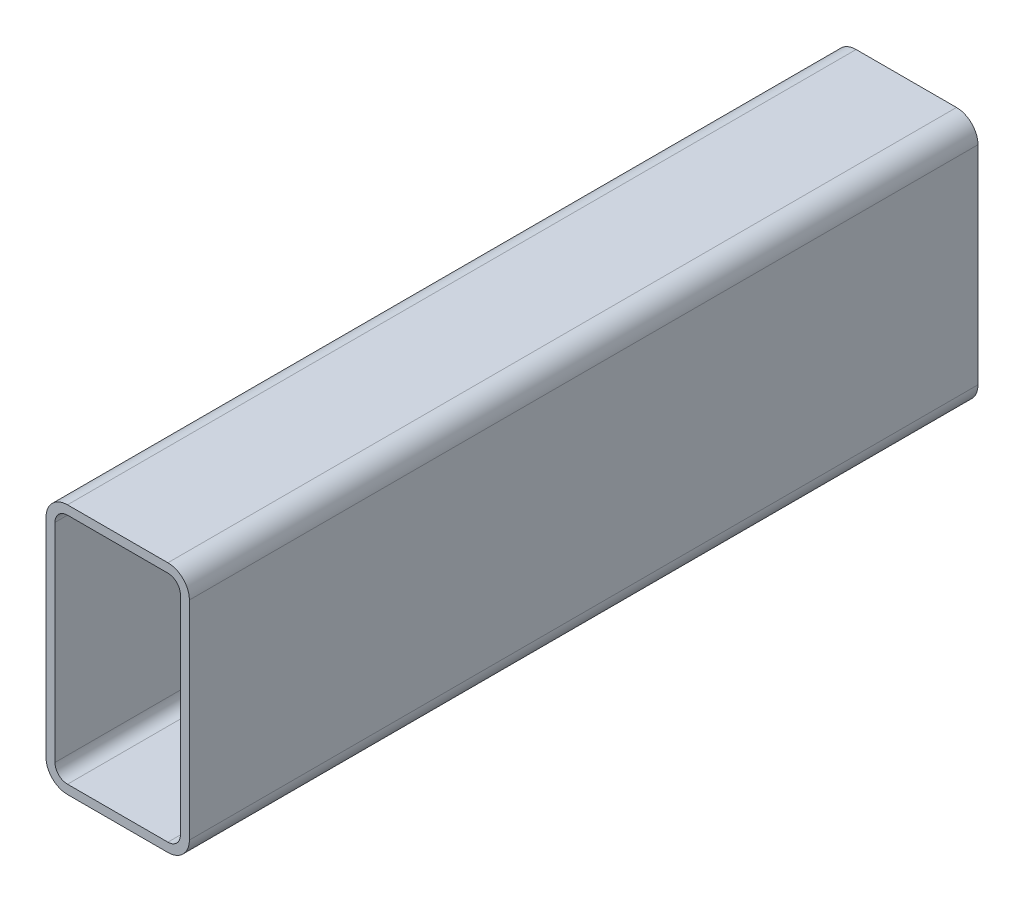
SolidWorks part; units mm, degrees
material "1.0037 (S235JR)"
ref_plane "Płaszczyzna przednia" through (0, 0, 0) normal (0, 0, 1) x (1, 0, 0)
ref_plane "Płaszczyzna górna" through (0, 0, 0) normal (0, 1, 0) x (1, 0, 0)
ref_plane "Płaszczyzna prawa" through (0, 0, 0) normal (1, 0, 0) x (0, 0, -1)
sketch "Szkic2" plane through (0, 0, 0) normal (0, 0, 1) x (1, 0, 0)
  line L0 (10, 450) -> (70, 450) construction
  line L1 (12, 450) -> (68, 450)
  line L2 (0, 438) -> (0, 322)
  line L3 (12, 310) -> (68, 310)
  line L4 (80, 438) -> (80, 322)
  line L5 (0, 450) -> (0, 0) construction
  line L6 (80, 450) -> (80, 0) construction
  line L7 (12, 445) -> (68, 445)
  line L8 (75, 438) -> (75, 322)
  line L9 (12, 315) -> (68, 315)
  line L10 (5, 438) -> (5, 322)
  arc A0 (0, 322) -> (12, 310) centre (12, 322) ccw
  arc A1 (80, 322) -> (68, 310) centre (68, 322) cw
  arc A2 (80, 438) -> (68, 450) centre (68, 438) ccw
  arc A3 (12, 450) -> (0, 438) centre (12, 438) ccw
  arc A4 (75, 438) -> (68, 445) centre (68, 438) ccw
  arc A5 (75, 322) -> (68, 315) centre (68, 322) cw
  arc A6 (5, 322) -> (12, 315) centre (12, 322) ccw
  arc A7 (12, 445) -> (5, 438) centre (12, 438) ccw
  dimension "D1" = 12
  dimension "D2" = 140
  dimension "D3" = 5
extrude "Dodanie-wyciągnięcie1" add sketch "Szkic2" along normal blind 440
